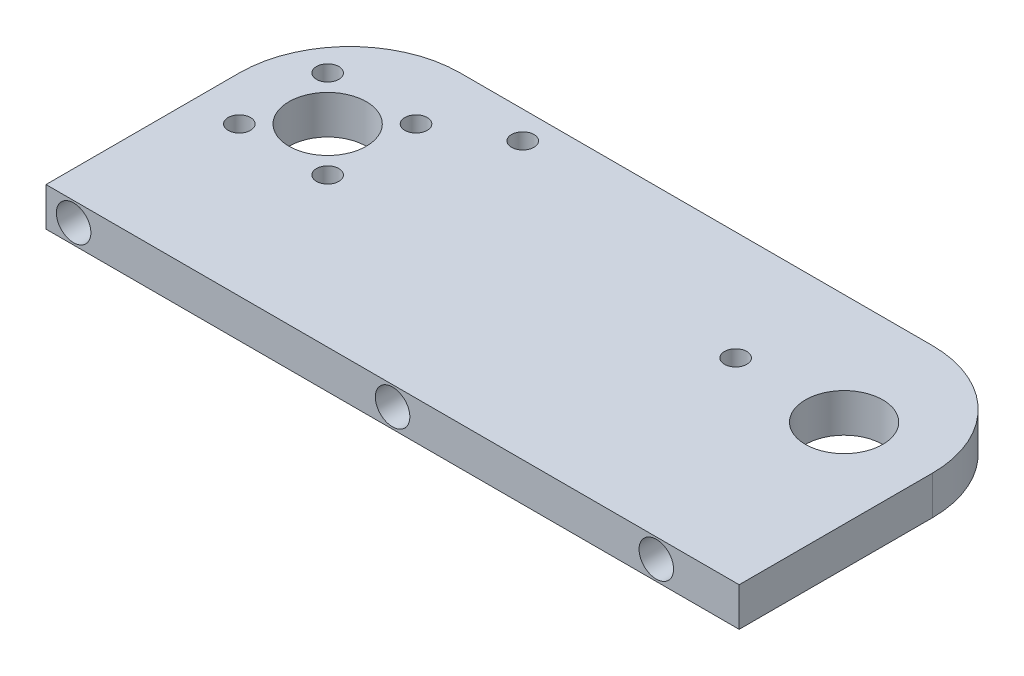
SolidWorks part; units mm, degrees
ref_plane "Front Plane" through (0, 0, 0) normal (0, 0, 1) x (1, 0, 0)
ref_plane "Top Plane" through (0, 0, 0) normal (0, 1, 0) x (1, 0, 0)
ref_plane "Right Plane" through (0, 0, 0) normal (1, 0, 0) x (0, 0, -1)
sketch "Sketch2" plane through (0, 0, 0) normal (0, 1, 0) x (1, 0, 0)
  line L6 (36.1891, 45.8964) -> (129.7012, 45.8964)
  line L7 (36.1891, 17.8964) -> (127.3685, 18.0921)
  line L8 (36.1891, 31.8964) -> (11.1891, 31.8964) construction
  line L9 (11.1891, 31.8964) -> (11.1891, 51.8964) construction
  line L10 (129.7012, 31.8964) -> (154.7012, 31.8964) construction
  line L11 (154.7012, 31.8964) -> (154.7012, 11.8964) construction
  line L12 (11.1891, 11.8964) -> (11.1891, -3.1036)
  line L13 (11.1891, 51.8964) -> (154.7012, 51.8964)
  line L14 (11.1891, 51.8964) -> (11.1891, 11.8964)
  line L15 (11.1891, 11.8964) -> (154.7012, 11.8964)
  line L16 (154.7012, 51.8964) -> (154.7012, 11.8964)
  line L17 (154.7012, 11.8964) -> (104.7012, 11.8964)
  line L18 (154.7012, 11.8964) -> (154.7012, -3.1036)
  line L19 (154.7012, -3.1036) -> (104.7012, -3.1036)
  line L21 (11.1891, -3.1036) -> (104.7012, -3.1036)
  line L22 (11.1891, 51.8964) -> (20.1891, 51.8964)
  line L23 (20.1891, 51.8964) -> (20.1891, 11.8964)
  line L24 (145.7012, 51.8964) -> (145.7012, 11.8964)
  line L25 (20.1891, 11.8964) -> (20.1891, -3.1036)
  line L26 (145.7012, 11.8964) -> (145.7012, -3.1036)
  arc A2 (36.1891, 45.8964) -> (36.1891, 17.8964) centre (36.1891, 31.8964) ccw
  arc A3 (127.3685, 18.0921) -> (129.7012, 45.8964) centre (129.7012, 31.8964) ccw
  circle A4 centre (36.1891, 31.8964) radius 7
  circle A5 centre (129.7012, 31.8964) radius 7
  dimension "D1" = 28
  dimension "D2" = 28
  dimension "D3" = 275
  dimension "D8" = 14
  dimension "D9" = 14
  dimension "D4" = 25
  dimension "D5" = 20
  dimension "D6" = 25
  dimension "D7" = 20
  dimension "D10" = 50
  dimension "D12" = 143.5121
  dimension "D13" = 9
  dimension "D14" = 9
  dimension "D15" = 15
extrude "Boss-Extrude1" add sketch "Sketch2" along normal blind 7 contours L7 A3 L6 A2 A5 A4 | L16 L13 L14 L15 A3 L7 A2 L6 | L12 L21 L19 L18 L15
sketch "Sketch4" plane through (0, 0, -51.8964) normal (0, 0, -1) x (-1, 0, 0)
  line L0 (-154.7012, 7) -> (-184.7012, 37)
  line L1 (-154.7012, 0) -> (-182.6115, 27.9103)
  line L2 (-20.1891, 7) -> (-145.7012, 7) construction
  line L3 (-20.1891, 0) -> (-145.7012, 0) construction
  line L4 (-182.6115, 27.9103) -> (-184.7012, 30)
  line L5 (-184.7012, 37) -> (-184.7012, 30)
  line L6 (-154.7012, 7) -> (-154.7012, 0) construction
  line L11 (-145.7012, 0) -> (-20.1891, 0)
  line L12 (-20.1891, 0) -> (-20.1891, 7)
  line L13 (-20.1891, 7) -> (-145.7012, 7)
  line L14 (-20.1891, 0) -> (-20.1891, 7)
  line L19 (-145.7012, 7) -> (-145.7012, 0)
  line L20 (-145.7012, 7) -> (-145.7012, 0)
  dimension "D1" = 135
  dimension "D2" = 135
  dimension "D3" = 30
  dimension "D4" = 0
fillet "Fillet4" radius 20
sketch "Sketch5" plane through (0, 7, 0) normal (0, 1, 0) x (1, 0, 0)
  line L0 (40.1891, 51.8964) -> (125.7012, 51.8964) construction
  line L1 (145.7012, 31.8964) -> (145.7012, -3.1036) construction
  circle A0 centre (109.8112, 32.1464) radius 2.025
  dimension "D3" = 4.05
  dimension "D1" = 19.75
  dimension "D2" = 35.89
extrude "Cut-Extrude1" cut sketch "Sketch5" against normal blind 10
sketch "Sketch6" plane through (0, 7, 0) normal (0, 1, 0) x (1, 0, 0)
  line L1 (28.1891, 23.8964) -> (44.1891, 23.8964)
  line L2 (28.1891, 23.8964) -> (28.1891, 39.8964)
  line L3 (28.1891, 39.8964) -> (44.1891, 39.8964)
  line L4 (44.1891, 23.8964) -> (44.1891, 39.8964)
  line L5 (28.1891, 23.8964) -> (44.1891, 39.8964) construction
  line L6 (28.1891, 39.8964) -> (44.1891, 23.8964) construction
  circle A0 centre (28.1891, 39.8964) radius 2.025
  circle A1 centre (44.1891, 39.8964) radius 2.025
  circle A2 centre (44.1891, 23.8964) radius 2.025
  circle A3 centre (28.1891, 23.8964) radius 2.025
  point P0 (36.1891, 31.8964)
  point P16 (36.1891, 31.8964)
  dimension "D3" = 4.05
  dimension "D1" = 16
  dimension "D2" = 16
  dimension "D4" = 4
extrude "Cut-Extrude2" cut sketch "Sketch6" against normal blind 33 contours A1 | A0 | A3 | A2
sketch "Sketch7" plane through (0, 0, 3.1036) normal (0, 0, 1) x (1, 0, 0)
  line L0 (20.1891, 0) -> (20.1891, 7) construction
  line L1 (145.7012, 7) -> (145.7012, 0) construction
  circle A0 centre (25.1891, 3.5) radius 3.125
  circle A1 centre (130.7012, 3.5) radius 3.125
  circle A2 centre (82.9451, 3.5) radius 3.125
  dimension "D1" = 6.25
  dimension "D3" = 6.25
  dimension "D5" = 6.25
  dimension "D2" = 5
  dimension "D4" = 15
extrude "Cut-Extrude3" cut sketch "Sketch7" against normal blind 4.7
sketch "Sketch8" plane through (0, 7, 0) normal (0, 1, 0) x (1, 0, 0)
  line L0 (40.1891, 51.8964) -> (125.7012, 51.8964) construction
  circle A0 centre (56.5147, 46.8964) radius 2.025
  dimension "D1" = 4.05
  dimension "D2" = 5
extrude "Cut-Extrude4" cut sketch "Sketch8" against normal blind 7
